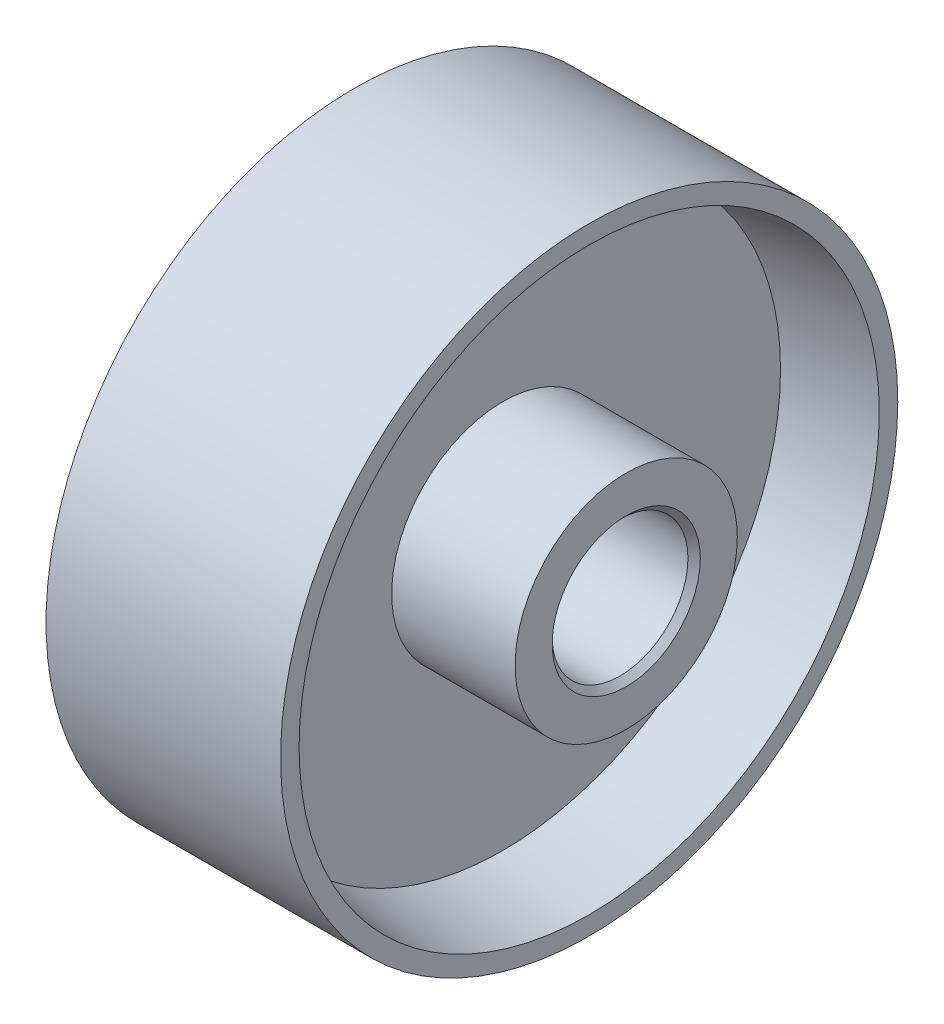
SolidWorks part; units mm, degrees
material "AISI 1020"
ref_plane "Plan de face" through (0, 0, 0) normal (0, 0, 1) x (1, 0, 0)
ref_plane "Plan de dessus" through (0, 0, 0) normal (0, 1, 0) x (1, 0, 0)
ref_plane "Plan de droite" through (0, 0, 0) normal (1, 0, 0) x (0, 0, -1)
sketch "Esquisse1" plane through (0, 0, 0) normal (0, 0, 1) x (1, 0, 0)
  line L0 (-40.6358, 0) -> (42.4026, 0) construction
  line L1 (-25, 11) -> (25, 11)
  line L2 (25, 11) -> (25, 18)
  line L3 (25, 18) -> (5, 18)
  line L4 (5, 18) -> (5, 45)
  line L5 (5, 45) -> (19, 47)
  line L6 (19, 47) -> (19, 50)
  line L7 (19, 50) -> (-19, 50)
  line L8 (-19, 50) -> (-19, 47)
  line L9 (-19, 47) -> (-5, 45)
  line L10 (-5, 45) -> (-5, 18)
  line L11 (-5, 18) -> (-25, 18)
  line L12 (-25, 18) -> (-25, 11)
  point P8 (0, 11)
  dimension "D1" = 22
  dimension "D2" = 36
  dimension "D3" = 100
  dimension "D4" = 3
  dimension "D5" = 5
  dimension "D6" = 38
  dimension "D7" = 10
  dimension "D8" = 50
revolve "Révolution1" add sketch "Esquisse1" angle 360 about L0
chamfer "Chanfrein1" distance 1 angle 45 2 edges at (-25, 0, -11) (25, 0, -11)
